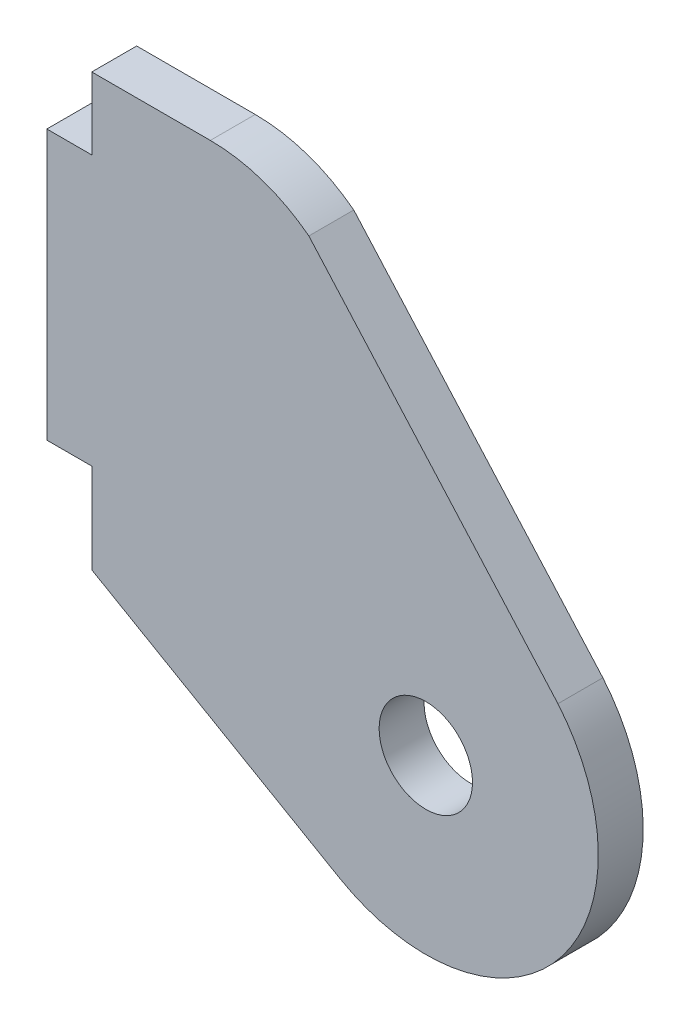
SolidWorks part; units mm, degrees
material "AISI 4130 Steel, annealed at 865C"
ref_plane "X-Y Datum" through (0, 0, 0) normal (0, 0, 1) x (1, 0, 0)
ref_plane "X-Z Datum" through (0, 0, 0) normal (0, 1, 0) x (1, 0, 0)
ref_plane "Y-Z Datum" through (0, 0, 0) normal (1, 0, 0) x (0, 0, -1)
sketch "Sketch1" plane through (0, 0, 0) normal (0, 0, 1) x (1, 0, 0)
  line L8 (-79.4095, -48.8706) -> (-79.4095, -29.8206)
  line L9 (-79.4095, -29.8206) -> (-76.2345, -29.8206)
  line L10 (-76.2345, -29.8206) -> (-76.2345, -24.7406)
  line L11 (-76.2345, -24.7406) -> (-67.8525, -24.7406)
  line L12 (-79.4095, -48.8706) -> (-76.2345, -48.8706)
  line L13 (-76.2345, -48.8706) -> (-76.2345, -55.2206)
  line L14 (-76.2345, -55.2206) -> (-58.7169, -65.3344)
  line L18 (-60.8897, -27.1062) -> (-43.2813, -46.9389)
  arc A2 (-58.7169, -65.3344) -> (-43.2813, -46.9389) centre (-52.6209, -54.7758) ccw
  arc A5 (-67.8525, -24.7406) -> (-60.8897, -27.1062) centre (-67.8525, -36.1706) cw
  dimension "D7" = 12.192
  dimension "D9" = 11.43
  dimension "D1" = 19.05
  dimension "D2" = 5.08
  dimension "D3" = 6.35
  dimension "D4" = 120
  dimension "D5" = 26.7886
  dimension "D8" = 8.382
  dimension "D10" = 37.53
  dimension "D11" = 3.175
  dimension "D12" = 3.175
extrude "Boss-Extrude1" add sketch "Sketch1" along normal blind 3.175
hole_wizard "M6 Clearance Hole1" positions "Sketch2" profile "Sketch3" hole size "M6" standard "ANSI Metric"
sketch "Sketch2" plane through (0, 0, 0) normal (0, 0, -1) x (-1, 0, 0)
  point P0 (52.6209, -54.7758)
sketch "Sketch3" plane through (-52.6209, -54.7758, 0) normal (1, 0, 0) x (0, 1, 0)
  line L0 (0, 0) -> (0, 5.2848)
  line L1 (0, 5.2848) -> (3.3, 3.302)
  line L2 (3.3, 3.302) -> (3.3, 0)
  line L5 (3.3, 0) -> (0, 0)
  line L10 (0, 5.2848) -> (-3.3, 3.302) construction
  line L11 (0, -6.35) -> (0, 107.95) construction
  dimension "Hole Dia." = 6.6
  dimension "Hole Depth" = 3.302
  dimension "Drill Angle" = 118
